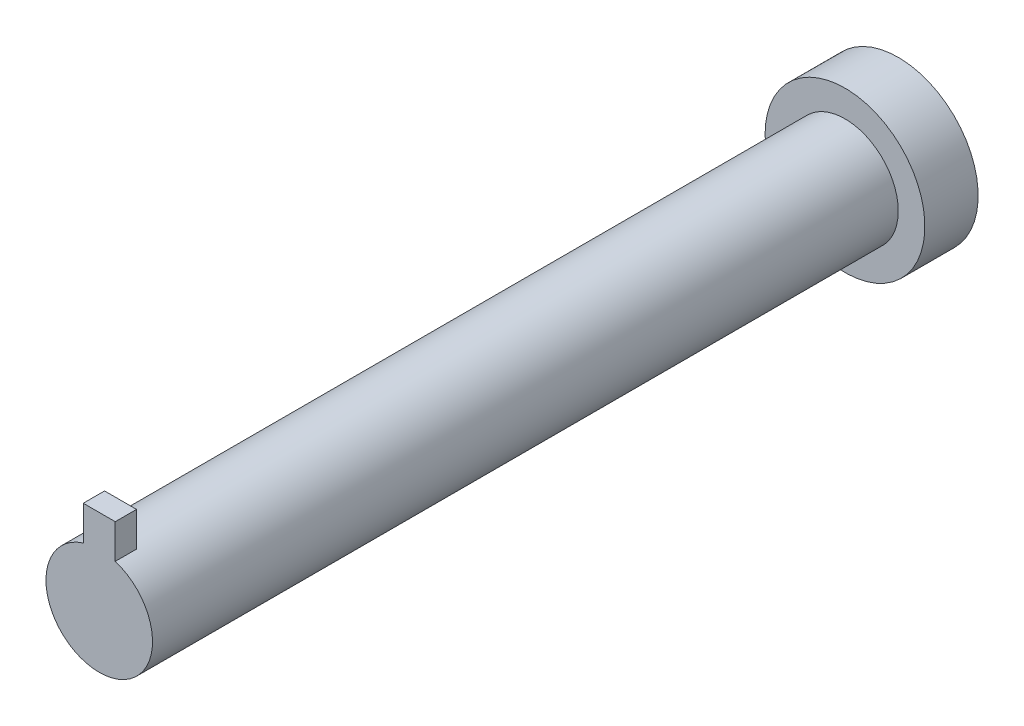
SolidWorks part; units mm, degrees
ref_plane "Ön Düzlem" through (0, 0, 0) normal (0, 0, 1) x (1, 0, 0)
ref_plane "Üst Düzlem" through (0, 0, 0) normal (0, 1, 0) x (1, 0, 0)
ref_plane "Sağ Düzlem" through (0, 0, 0) normal (1, 0, 0) x (0, 0, -1)
sketch "Çizim1" plane through (0, 0, 0) normal (0, 0, 1) x (1, 0, 0)
  circle A0 centre (0, 0) radius 5
  dimension "D1" = 10
extrude "Yükseklik-Ekstrüzyon1" add sketch "Çizim1" along normal blind 70
sketch "Çizim2" plane through (0, 0, 0) normal (0, 0, -1) x (-1, 0, 0)
  circle A0 centre (0, 0) radius 7.5
  dimension "D1" = 15
extrude "Yükseklik-Ekstrüzyon2" add sketch "Çizim2" along normal blind 5
sketch "Çizim3" plane through (0, 0, 0) normal (0, 1, 0) x (1, 0, 0)
  line L0 (-5, -70) -> (5, -70) construction
  line L1 (-1.5, -68) -> (1.5, -68)
  line L2 (-1.5, -68) -> (-1.5, -70)
  line L3 (-1.5, -70) -> (1.5, -70)
  line L4 (1.5, -68) -> (1.5, -70)
  dimension "D1" = 1.5
  dimension "D2" = 1.5
  dimension "D3" = 2
extrude "Yükseklik-Ekstrüzyon3" add sketch "Çizim3" along normal blind 8
